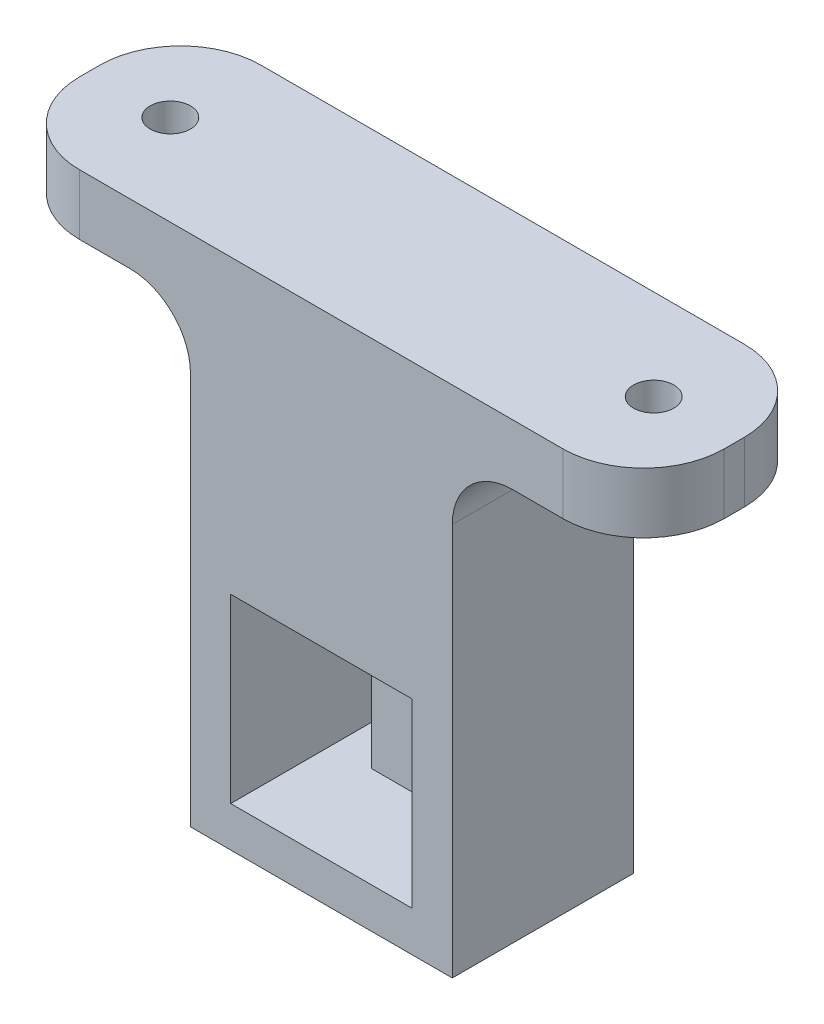
SolidWorks part; units mm, degrees
ref_plane "Front Plane" through (0, 0, 0) normal (0, 0, 1) x (1, 0, 0)
ref_plane "Top Plane" through (0, 0, 0) normal (0, 1, 0) x (1, 0, 0)
ref_plane "Right Plane" through (0, 0, 0) normal (1, 0, 0) x (0, 0, -1)
sketch "Sketch1" plane through (0, 0, -30) normal (0, 0, -1) x (-1, 0, 0)
  line L8 (-2.5, 10.5) -> (-2.5, 1.5)
  line L9 (-2.5, 1.5) -> (2.5, 1.5)
  line L10 (2.5, 1.5) -> (2.5, 10.5)
  line L11 (2.5, 10.5) -> (-2.5, 10.5)
  line L16 (4.5, 1.5) -> (4.5, 10.5)
  line L17 (-4.5, 1.5) -> (4.5, 1.5)
  line L18 (-4.5, 10.5) -> (-4.5, 1.5)
  line L19 (4.5, 10.5) -> (-4.5, 10.5)
  line L28 (6.5, -0.5) -> (6.5, 12.5)
  line L29 (-6.5, -0.5) -> (6.5, -0.5)
  line L30 (-6.5, 12.5) -> (-6.5, -0.5)
  line L31 (6.5, 12.5) -> (-6.5, 12.5)
  point P6 (0, -0.5)
  point P8 (4.5, 6)
  point P10 (6.5, 6)
  point P11 (0, 1.5)
  point P12 (-4.8759, 10.5)
  point P13 (-13.8207, 1.5)
  point P15 (0, 1.5)
  point P17 (2.5, 1.5)
  point P21 (-2.5, 1.5)
  point P22 (2.5, 10.5)
  line M13 (-2.5, 10.5) -> (-2.5, 1.5)
  line M14 (-2.5, 1.5) -> (2.5, 1.5)
  line M15 (2.5, 1.5) -> (2.5, 10.5)
  line M16 (2.5, 10.5) -> (-2.5, 10.5)
  dimension "D1" = 0.5
  dimension "D2" = 13
  dimension "D3" = 13
  dimension "D4" = 9
  dimension "D5" = 9
  dimension "D6" = 5
extrude "Boss-Extrude1" add sketch "Sketch1" along normal blind 4 contours M16 M13 M14 M15 | L28 L31 L30 L29 L19 L16 L17 L18 M14 M16
sketch "Sketch2" plane through (0, 0, -30) normal (0, 0, 1) x (1, 0, 0)
  line L0 (-4.5, 10.5) -> (-4.5, 1.5)
  line L1 (-4.5, 1.5) -> (4.5, 1.5)
  line L2 (4.5, 1.5) -> (4.5, 10.5)
  line L3 (4.5, 10.5) -> (-4.5, 10.5)
  line L4 (-6.5, 12.5) -> (-6.5, -0.5)
  line L5 (-6.5, -0.5) -> (6.5, -0.5)
  line L6 (6.5, -0.5) -> (6.5, 12.5)
  line L7 (6.5, 12.5) -> (-6.5, 12.5)
  line L8 (-6.5, 12.5) -> (-6.5, -0.5)
  line L9 (-6.5, -0.5) -> (6.5, -0.5)
  line L10 (6.5, -0.5) -> (6.5, 12.5)
  line L11 (6.5, 12.5) -> (-6.5, 12.5)
  dimension "D1" = 0
  dimension "D2" = 2
extrude "Boss-Extrude2" add sketch "Sketch2" along normal blind 5
sketch "Sketch3" plane through (0, 12.5, 0) normal (0, 1, 0) x (1, 0, 0)
  line L4 (-6.5, 34) -> (-6.5, 25)
  line L5 (-6.5, 25) -> (6.5, 25)
  line L6 (6.5, 25) -> (6.5, 34)
  line L7 (6.5, 34) -> (-6.5, 34)
  line L8 (-6.5, 34) -> (-6.5, 25)
  line L9 (-6.5, 25) -> (6.5, 25)
  line L10 (6.5, 25) -> (6.5, 34)
  line L11 (6.5, 34) -> (-6.5, 34)
  dimension "D1" = 0
extrude "Boss-Extrude3" add sketch "Sketch3" along normal up to surface (12.5 mm away)
sketch "Sketch4" plane through (0, 25, 0) normal (0, 1, 0) x (1, 0, 0)
  line L0 (-16, 29) -> (-16, -24) construction
  line L1 (-12, 25) -> (12, 25)
  line L2 (-16, 29) -> (-16, 30)
  line L3 (-12, 34) -> (12, 34)
  line L4 (16, 29) -> (16, 30)
  line L5 (16, -24) -> (16, 29) construction
  line L6 (6.5, 25) -> (-6.5, 25) construction
  line L7 (12, 33) -> (-12, 33) construction
  arc A0 (12, 34) -> (16, 30) centre (12, 30) cw
  arc A1 (12, 25) -> (16, 29) centre (12, 29) ccw
  arc A2 (-12, 25) -> (-16, 29) centre (-12, 29) cw
  arc A3 (-16, 30) -> (-12, 34) centre (-12, 30) cw
  point P17 (16, 25)
  point P20 (-16, 25)
  dimension "D1" = 4
extrude "Boss-Extrude4" add sketch "Sketch4" against normal blind 3
fillet "Fillet1" radius 3 2 edges at (6.5, 22, -29.5) (-6.5, 22, -29.5)
sketch "Sketch5" plane through (0, 22, 0) normal (0, -1, 0) x (1, 0, 0)
  line L0 (-16, -30) -> (-16, -29) construction
  line L1 (16, -29) -> (16, -30) construction
  circle A0 centre (-12, -29.5) radius 1
  circle A1 centre (12, -29.5) radius 1
  point P6 (-16, -29.5)
  point P14 (16, -29.5)
  dimension "D1" = 2
extrude "Cut-Extrude1" cut sketch "Sketch5" against normal through all
